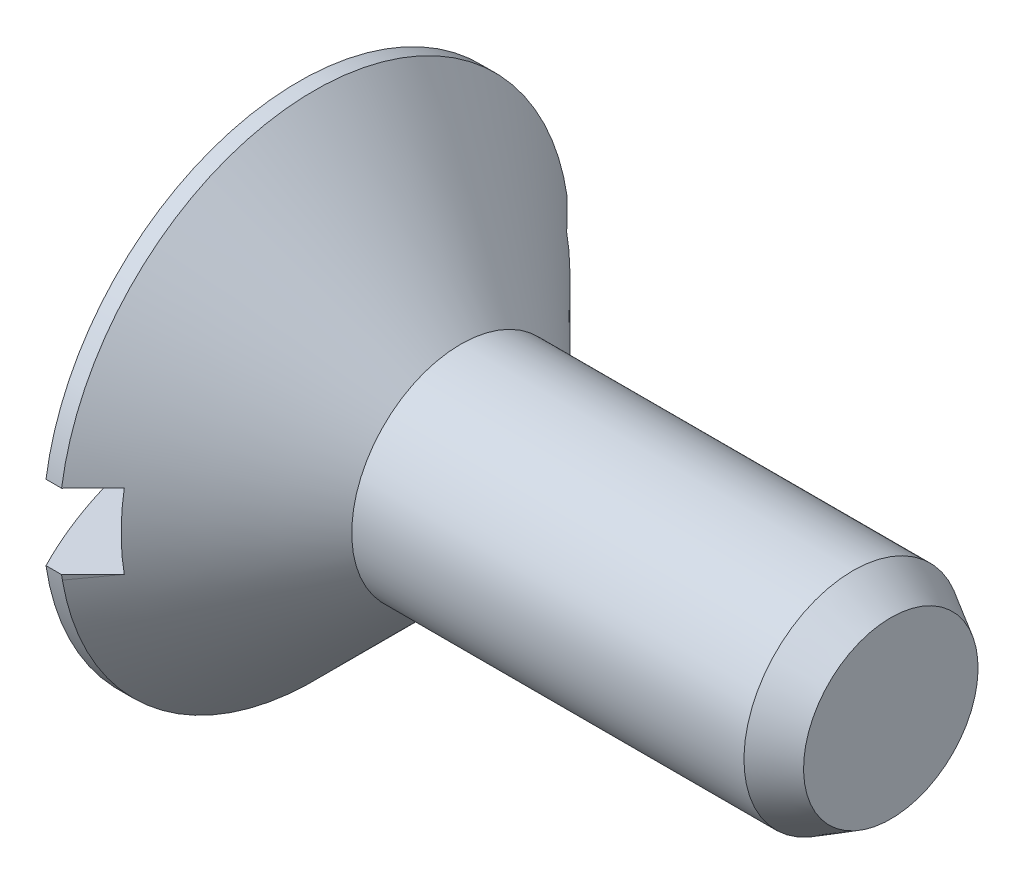
SolidWorks part; units mm, degrees
ref_plane "Front" through (0, 0, 0) normal (0, 0, 1) x (1, 0, 0)
ref_plane "Top" through (0, 0, 0) normal (0, 1, 0) x (1, 0, 0)
ref_plane "Right" through (0, 0, 0) normal (1, 0, 0) x (0, 0, -1)
sketch "Sketch1" plane through (0, 0, 0) normal (0, 0, 1) x (1, 0, 0)
  line L0 (0, 4.1) -> (0.25, 4.1)
  line L1 (0.25, 4.1) -> (2.6, 1.75)
  line L2 (2.6, 1.75) -> (9.5, 1.75)
  line L3 (9.5, 1.75) -> (9.5, 0)
  line L4 (9.5, 0) -> (0, 0)
  line L5 (0, 0) -> (0, 4.1) construction
  line L6 (6.6207, 0) -> (-1, 0) construction
  line L7 (-1, 0) -> (-1, -0.1422) construction
  line L8 (0, 0) -> (-1, 0)
  arc A1 (0, 4.1) -> (-1, 0) centre (7.905, 0) ccw
  dimension "D1" = 45
  dimension "d" = 3.5
  dimension "dK" = 8.2
  dimension "l" = 9.5
  dimension "f" = 1
  dimension "k" = 2.6
revolve "Revolve1" add sketch "Sketch1" angle 360 about L6
cosmetic thread "ThreadCosmetic" [suppressed] parameters "D2"=3.2
sketch "Sketch2" plane through (0, 0, 0) normal (0, 0, 1) x (1, 0, 0)
  line L1 (-1, 0.6) -> (0.75, 0.6)
  line L2 (-1, 0.6) -> (-1, -0.6)
  line L3 (-1, -0.6) -> (0.75, -0.6)
  line L4 (0.75, 0.6) -> (0.75, -0.6)
  line L5 (0, 0) -> (-1, 0) construction
  arc A0 (0, 4.1) -> (-1, 0) centre (7.905, 0) ccw construction
  dimension "n" = 1.2
  dimension "t" = 1.75
extrude "Cut-Extrude1" cut sketch "Sketch2" against normal through all and the other way through all
chamfer "Chamfer1" distance 0.35 angle 60 1 edges at (9.5, 1.75, 0)
sketch "Sketch4" plane through (0, 0, 0) normal (0, 0, 1) x (1, 0, 0)
  line L0 (3.0424, 1.6) -> (2.7347, 1.6)
  line L1 (2.7347, 1.6) -> (2.6481, 1.75)
  line L2 (3.0424, 1.6) -> (3.129, 1.75)
  line L3 (2.6481, 1.75) -> (2.6481, 2)
  line L4 (3.129, 1.75) -> (3.129, 2)
  line L5 (2.6481, 2) -> (3.129, 2)
  line L6 (2.8886, 1.6) -> (2.8886, 0) construction
  line L7 (0, 0) -> (7.3035, 0) construction
  line L9 (2.6, 1.75) -> (2.6, -1.75) construction
  line L12 (8.8938, 1.75) -> (2.6, 1.75) construction
  dimension "D2" = 60
  dimension "D3" = 0.25
  dimension "advance" = 0.4809
  dimension "minordia" = 3.2
  dimension "threadstart" = 0.2886
revolve "ThreadSchematic" [suppressed] cut sketch "Sketch4" angle 360 about L7
pattern_linear "ThdSchPat" [suppressed] count 15 spacing 0.4809 along (-1, 0, 0)
sketch "Sketch3" plane through (0, 0, 0) normal (0, 0, 1) x (1, 0, 0)
  line L0 (2.6, 1.75) -> (9.5, 1.75) construction
  line L2 (7.5, 1.75) -> (8, 1.75) construction
  line L3 (9.5, 1.75) -> (9.5, 0) construction
  line L4 (8, 1.75) -> (9.5, 0)
  line L5 (2.9, 0) -> (5.4301, 0) construction
  line L6 (9.5, 0) -> (9.7, 0)
  line L7 (9.7, 0) -> (9.7, 1.75)
  line L8 (9.7, 1.75) -> (9.5, 1.75)
  line L9 (8, 1.75) -> (9.5, 1.75)
  dimension "y" = 2
  dimension "D1" = 0.5
revolve "EndCone" [suppressed] cut sketch "Sketch3" angle 360 about L5
equation "\"minordia@Sketch4\" = \"D2@ThreadCosmetic\""
equation "\"D1@Chamfer1\" = \"d@Sketch1\" / 10"
equation "\"D1@Sketch3\" = \"y@Sketch3\" / 4"
equation "\"threadstart@Sketch4\" = \"advance@Sketch4\"*0.6"
equation "\"D1@ThdSchPat\" = int(((\"l@Sketch1\"-\"k@Sketch1\")/\"advance@Sketch4\") + 0.999)"
equation "\"D3@ThdSchPat\" = \"advance@Sketch4\""
